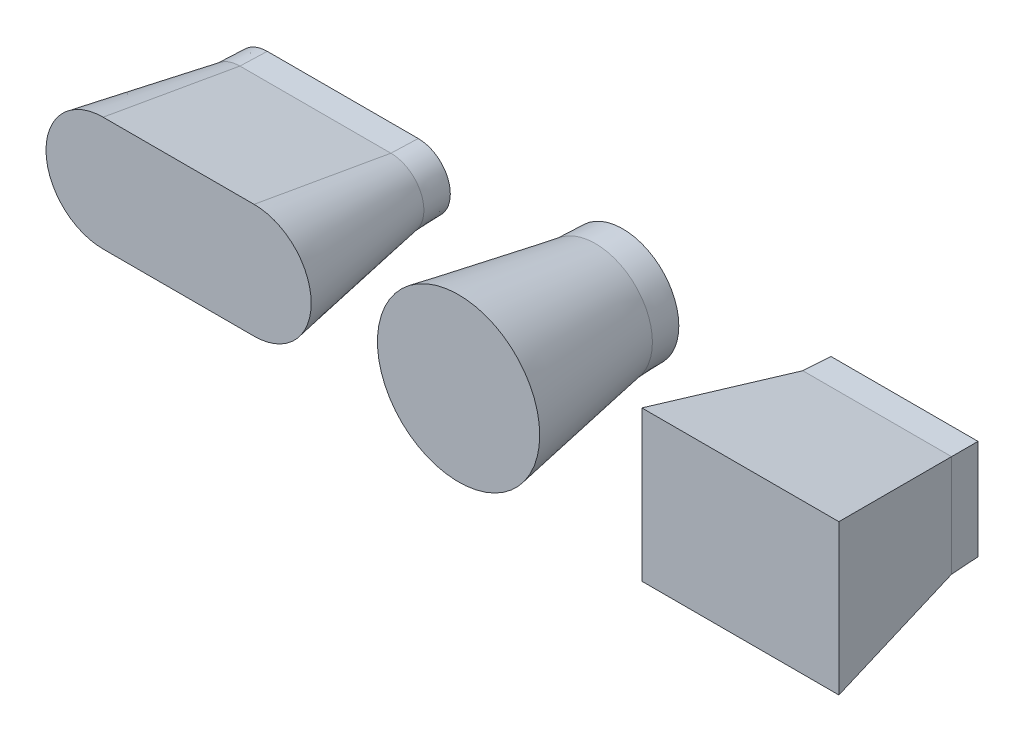
SolidWorks part; units mm, degrees
ref_plane "Front Plane" through (0, 0, 0) normal (0, 0, 1) x (1, 0, 0)
ref_plane "Top Plane" through (0, 0, 0) normal (0, 1, 0) x (1, 0, 0)
ref_plane "Right Plane" through (0, 0, 0) normal (1, 0, 0) x (0, 0, -1)
sketch "Sketch4" plane through (0, 0, 0) normal (0, 0, 1) x (1, 0, 0)
  line L0 (-155.881, 12.9901) -> (-100.7066, 12.9901) construction
  line L5 (-155.881, 25.0427) -> (-100.7066, 25.0427)
  line L6 (-155.881, 0.9374) -> (-100.7066, 0.9374)
  line L8 (49.8176, 31.4708) -> (104.1885, 31.4708)
  line L9 (49.8176, 31.4708) -> (49.8176, -5.7585)
  line L10 (49.8176, -5.7585) -> (104.1885, -5.7585)
  line L11 (104.1885, 31.4708) -> (104.1885, -5.7585)
  arc A0 (-155.881, 25.0427) -> (-155.881, 0.9374) centre (-155.881, 12.9901) ccw
  arc A1 (-100.7066, 0.9374) -> (-100.7066, 25.0427) centre (-100.7066, 12.9901) ccw
  circle A2 centre (-25.9802, 12.9901) radius 20.8363
  point P2 (-128.2938, 12.9901)
extrude "Boss-Extrude1" add sketch "Sketch4" along normal blind 50 draft 10 and the other way blind 10 draft 2
